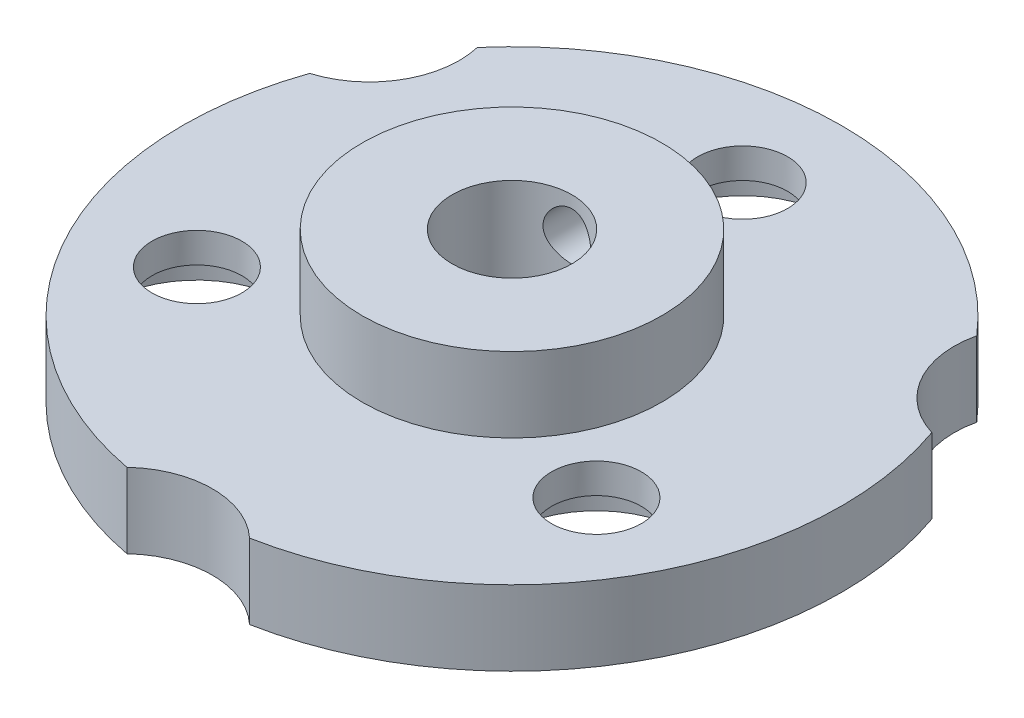
SolidWorks part; units mm, degrees
ref_plane "Plano frontal" through (0, 0, 0) normal (0, 0, 1) x (1, 0, 0)
ref_plane "Plano superior" through (0, 0, 0) normal (0, 1, 0) x (1, 0, 0)
ref_plane "Plano direito" through (0, 0, 0) normal (1, 0, 0) x (0, 0, -1)
sketch "Esboço1" plane through (0, 0, 0) normal (0, 1, 0) x (1, 0, 0)
  circle A0 centre (0, 0) radius 11
  dimension "D1" = 22
extrude "Ressalto-extrusão1" add sketch "Esboço1" along normal blind 2.5
sketch "Esboço3" plane through (0, 2.5, 0) normal (0, 1, 0) x (1, 0, 0)
  circle A1 centre (0, 7.7) radius 1.5
  circle A2 centre (6.6684, -3.85) radius 1.5
  circle A3 centre (-6.6684, -3.85) radius 1.5
  dimension "D3" = 3
  dimension "D1" = 7.7
  dimension "D2" = 7.7
extrude "Corte-extrusão1" cut sketch "Esboço3" against normal blind 2.5
sketch "Esboço18" plane through (0, 2.5, 0) normal (0, 1, 0) x (1, 0, 0)
  circle A0 centre (0, 0) radius 5
  dimension "D1" = 10
extrude "Ressalto-extrusão5" add sketch "Esboço18" along normal blind 2.5
sketch "Esboço20" plane through (0, 5, 0) normal (0, 1, 0) x (1, 0, 0)
  circle A0 centre (0, 0) radius 2
  dimension "D1" = 4
extrude "Corte-extrusão5" cut sketch "Esboço20" against normal blind 5.5
hole_wizard "Broca de rosquear para tarraxa de M2x0.42" positions "3DSketch3" profile "Esboço21" hole size "M2x0.4" standard "Ansi Metric"
sketch3d "3DSketch3"
  point P0 (0.0026, 3.793, -5)
sketch "Esboço21" plane through (0.0026, 3.793, -5) normal (0, 1, 0) x (-1, 0, -0.0005)
  line L0 (0, 0) -> (0, 3)
  line L1 (0, 3) -> (0.8, 3)
  line L2 (0.8, 3) -> (0.8, 0)
  line L5 (0.8, 0) -> (0, 0)
  line L11 (0, -6.35) -> (0, 107.95) construction
  dimension "Thru Hole Dia." = 1.6
  dimension "Thru Hole Depth" = 3
sketch "Esboço22" plane through (0, 2.5, 0) normal (0, 1, 0) x (1, 0, 0)
  circle A1 centre (-11.2583, 6.5) radius 3
  circle A2 centre (0, -13) radius 3
  circle A3 centre (11.2583, 6.5) radius 3
  dimension "D1" = 6
extrude "Corte-extrusão6" cut sketch "Esboço22" against normal blind 5.5
sketch "Esboço23" plane through (0, 0, 0) normal (0, -1, 0) x (-1, 0, 0)
  circle A0 centre (-6.6684, -3.85) radius 3
  circle A1 centre (6.6684, -3.85) radius 3
  circle A2 centre (0, 7.7) radius 3
  dimension "D1" = 6
extrude "Corte-extrusão7" cut sketch "Esboço23" against normal blind 1.5
